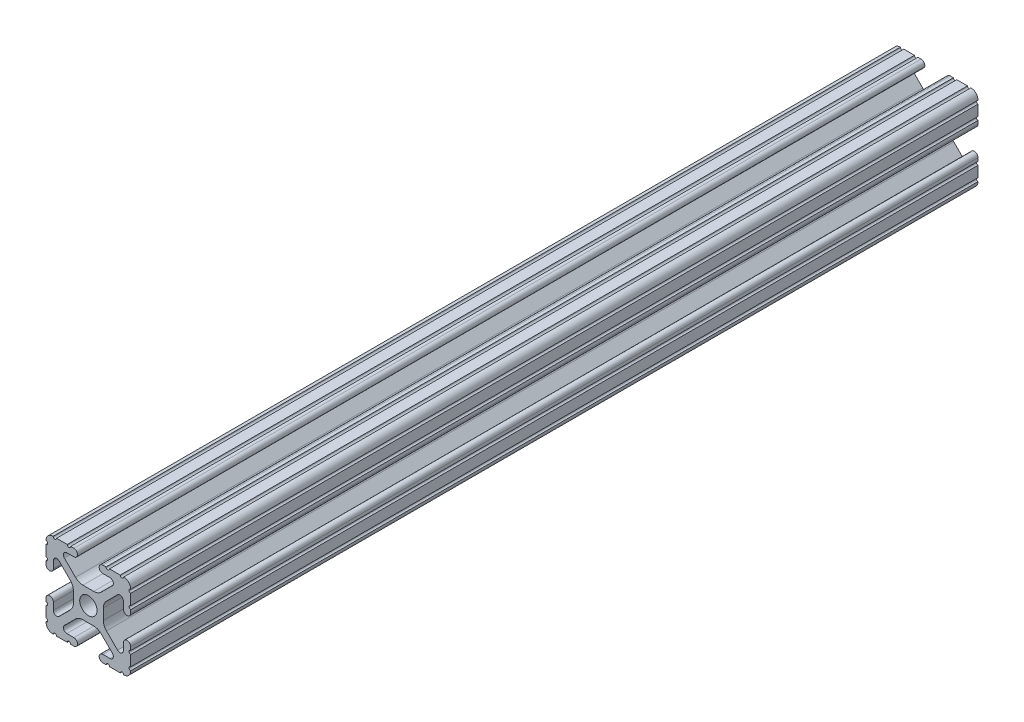
SolidWorks part; units mm, degrees
ref_plane "Front Plane" through (0, 0, 0) normal (0, 0, 1) x (1, 0, 0)
ref_plane "Top Plane" through (0, 0, 0) normal (0, 1, 0) x (1, 0, 0)
ref_plane "Right Plane" through (0, 0, 0) normal (1, 0, 0) x (0, 0, -1)
ref_plane "Plane1" through (0, 0, -254) normal (0, 0, -1) x (-1, 0, 0)
sketch "Sketch1" plane through (0, 0, -254) normal (0, 0, -1) x (-1, 0, 0)
  line L0 (12.7, -9.5504) -> (12.7, -6.3331)
  line L1 (12.7, -5.3171) -> (12.7, -4.3434)
  line L2 (10.4902, -4.3434) -> (10.4902, -6.4748)
  line L3 (8.7558, -7.1932) -> (5.4257, -3.8632)
  line L4 (4.4958, -1.6181) -> (4.4958, 1.6181)
  line L5 (5.4257, 3.8632) -> (8.7558, 7.1932)
  line L6 (10.4902, 6.4748) -> (10.4902, 4.3434)
  line L7 (12.7, 4.3434) -> (12.7, 5.3171)
  line L8 (12.7, 6.3331) -> (12.7, 9.5504)
  line L9 (9.5504, 12.7) -> (6.3331, 12.7)
  line L10 (5.3171, 12.7) -> (4.3434, 12.7)
  line L11 (4.3434, 10.4902) -> (6.4748, 10.4902)
  line L12 (7.1932, 8.7558) -> (3.8632, 5.4257)
  line L13 (1.6181, 4.4958) -> (-1.6181, 4.4958)
  line L14 (-3.8632, 5.4257) -> (-7.1932, 8.7558)
  line L15 (-6.4748, 10.4902) -> (-4.3434, 10.4902)
  line L16 (-4.3434, 12.7) -> (-5.3171, 12.7)
  line L17 (-6.3331, 12.7) -> (-9.5504, 12.7)
  line L18 (-12.7, 9.5504) -> (-12.7, 6.3331)
  line L19 (-12.7, 5.3171) -> (-12.7, 4.3434)
  line L20 (-10.4902, 4.3434) -> (-10.4902, 6.4748)
  line L21 (-8.7558, 7.1932) -> (-5.4257, 3.8632)
  line L22 (-4.4958, 1.6181) -> (-4.4958, -1.6181)
  line L23 (-5.4257, -3.8632) -> (-8.7558, -7.1932)
  line L24 (-10.4902, -6.4748) -> (-10.4902, -4.3434)
  line L25 (-12.7, -4.3434) -> (-12.7, -5.3171)
  line L26 (-12.7, -6.3331) -> (-12.7, -9.5504)
  line L27 (-9.5504, -12.7) -> (-6.3331, -12.7)
  line L28 (-5.3171, -12.7) -> (-4.3434, -12.7)
  line L29 (-4.3434, -10.4902) -> (-6.4748, -10.4902)
  line L30 (-7.1932, -8.7558) -> (-3.8632, -5.4257)
  line L31 (-1.6181, -4.4958) -> (1.6181, -4.4958)
  line L32 (3.8632, -5.4257) -> (7.1932, -8.7558)
  line L33 (6.4748, -10.4902) -> (4.3434, -10.4902)
  line L34 (4.3434, -12.7) -> (5.3171, -12.7)
  line L35 (6.3331, -12.7) -> (9.5504, -12.7)
  arc A0 (12.6998, -10.5664) -> (12.7, -9.5504) centre (12.7, -10.0584) cw
  arc A1 (12.7, -6.3331) -> (12.7, -5.3171) centre (12.7, -5.8251) cw
  arc A2 (12.7, -4.3434) -> (10.4902, -4.3434) centre (11.5951, -4.3434) ccw
  arc A3 (10.4902, -6.4748) -> (8.7558, -7.1932) centre (9.4742, -6.4748) cw
  arc A4 (5.4257, -3.8632) -> (4.4958, -1.6181) centre (7.6708, -1.6181) cw
  arc A5 (4.4958, 1.6181) -> (5.4257, 3.8632) centre (7.6708, 1.6181) cw
  arc A6 (8.7558, 7.1932) -> (10.4902, 6.4748) centre (9.4742, 6.4748) cw
  arc A7 (10.4902, 4.3434) -> (12.7, 4.3434) centre (11.5951, 4.3434) ccw
  arc A8 (12.7, 5.3171) -> (12.7, 6.3331) centre (12.7, 5.8251) cw
  arc A9 (12.7, 9.5504) -> (12.6998, 10.5664) centre (12.7, 10.0584) cw
  arc A10 (12.6998, 10.5664) -> (10.5664, 12.6998) centre (10.5918, 10.5918) ccw
  arc A11 (10.5664, 12.6998) -> (9.5504, 12.7) centre (10.0584, 12.7) cw
  arc A12 (6.3331, 12.7) -> (5.3171, 12.7) centre (5.8251, 12.7) cw
  arc A13 (4.3434, 12.7) -> (4.3434, 10.4902) centre (4.3434, 11.5951) ccw
  arc A14 (6.4748, 10.4902) -> (7.1932, 8.7558) centre (6.4748, 9.4742) cw
  arc A15 (3.8632, 5.4257) -> (1.6181, 4.4958) centre (1.6181, 7.6708) cw
  arc A16 (-1.6181, 4.4958) -> (-3.8632, 5.4257) centre (-1.6181, 7.6708) cw
  arc A17 (-7.1932, 8.7558) -> (-6.4748, 10.4902) centre (-6.4748, 9.4742) cw
  arc A18 (-4.3434, 10.4902) -> (-4.3434, 12.7) centre (-4.3434, 11.5951) ccw
  arc A19 (-5.3171, 12.7) -> (-6.3331, 12.7) centre (-5.8251, 12.7) cw
  arc A20 (-9.5504, 12.7) -> (-10.5664, 12.6998) centre (-10.0584, 12.7) cw
  arc A21 (-10.5664, 12.6998) -> (-12.6998, 10.5664) centre (-10.5918, 10.5918) ccw
  arc A22 (-12.6998, 10.5664) -> (-12.7, 9.5504) centre (-12.7, 10.0584) cw
  arc A23 (-12.7, 6.3331) -> (-12.7, 5.3171) centre (-12.7, 5.8251) cw
  arc A24 (-12.7, 4.3434) -> (-10.4902, 4.3434) centre (-11.5951, 4.3434) ccw
  arc A25 (-10.4902, 6.4748) -> (-8.7558, 7.1932) centre (-9.4742, 6.4748) cw
  arc A26 (-5.4257, 3.8632) -> (-4.4958, 1.6181) centre (-7.6708, 1.6181) cw
  arc A27 (-4.4958, -1.6181) -> (-5.4257, -3.8632) centre (-7.6708, -1.6181) cw
  arc A28 (-8.7558, -7.1932) -> (-10.4902, -6.4748) centre (-9.4742, -6.4748) cw
  arc A29 (-10.4902, -4.3434) -> (-12.7, -4.3434) centre (-11.5951, -4.3434) ccw
  arc A30 (-12.7, -5.3171) -> (-12.7, -6.3331) centre (-12.7, -5.8251) cw
  arc A31 (-12.7, -9.5504) -> (-12.6998, -10.5664) centre (-12.7, -10.0584) cw
  arc A32 (-12.6998, -10.5664) -> (-10.5664, -12.6998) centre (-10.5918, -10.5918) ccw
  arc A33 (-10.5664, -12.6998) -> (-9.5504, -12.7) centre (-10.0584, -12.7) cw
  arc A34 (-6.3331, -12.7) -> (-5.3171, -12.7) centre (-5.8251, -12.7) cw
  arc A35 (-4.3434, -12.7) -> (-4.3434, -10.4902) centre (-4.3434, -11.5951) ccw
  arc A36 (-6.4748, -10.4902) -> (-7.1932, -8.7558) centre (-6.4748, -9.4742) cw
  arc A37 (-3.8632, -5.4257) -> (-1.6181, -4.4958) centre (-1.6181, -7.6708) cw
  arc A38 (1.6181, -4.4958) -> (3.8632, -5.4257) centre (1.6181, -7.6708) cw
  arc A39 (7.1932, -8.7558) -> (6.4748, -10.4902) centre (6.4748, -9.4742) cw
  arc A40 (4.3434, -10.4902) -> (4.3434, -12.7) centre (4.3434, -11.5951) ccw
  arc A41 (5.3171, -12.7) -> (6.3331, -12.7) centre (5.8251, -12.7) cw
  arc A42 (9.5504, -12.7) -> (10.5664, -12.6998) centre (10.0584, -12.7) cw
  arc A43 (10.5664, -12.6998) -> (12.6998, -10.5664) centre (10.5918, -10.5918) ccw
  circle A44 centre (0, 0) radius 2.6035
extrude "Boss-Extrude1" add sketch "Sketch1" against normal blind 254
